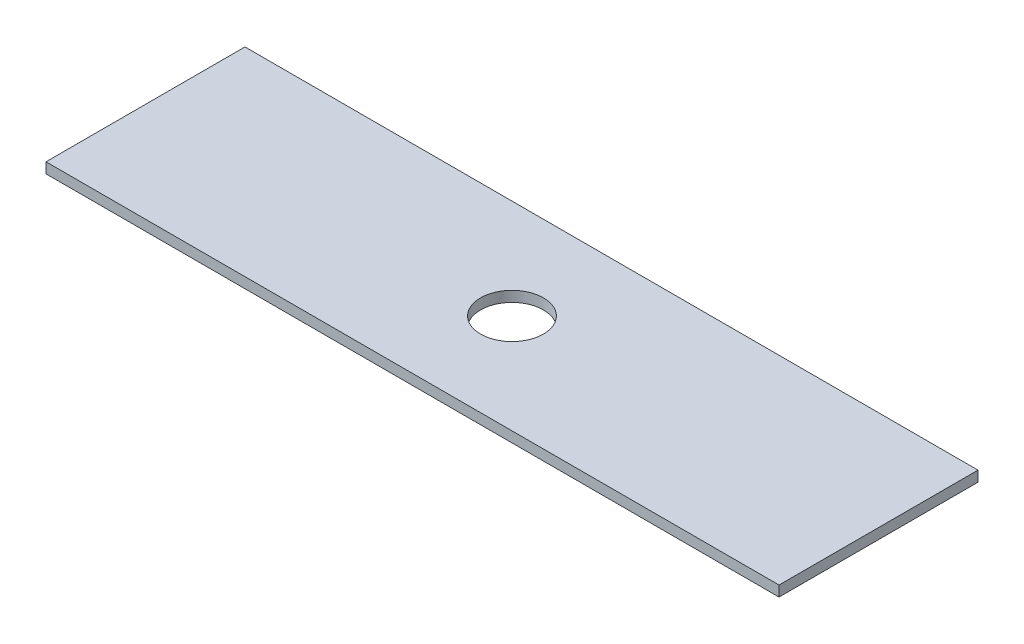
SolidWorks part; units mm, degrees
ref_plane "Alzado" through (0, 0, 0) normal (0, 0, 1) x (1, 0, 0)
ref_plane "Planta" through (0, 0, 0) normal (0, 1, 0) x (1, 0, 0)
ref_plane "Vista lateral" through (0, 0, 0) normal (1, 0, 0) x (0, 0, -1)
sketch "Croquis1" plane through (0, 0, 0) normal (0, 1, 0) x (1, 0, 0)
  line L1 (-350, -95) -> (350, -95)
  line L2 (-350, -95) -> (-350, 95)
  line L3 (-350, 95) -> (350, 95)
  line L4 (350, -95) -> (350, 95)
  line L5 (-350, -95) -> (350, 95) construction
  line L6 (-350, 95) -> (350, -95) construction
  point P0 (0, 0)
  dimension "D1" = 700
  dimension "D2" = 190
extrude "Saliente-Extruir1" add sketch "Croquis1" along normal blind 10
sketch "Croquis2" plane through (0, 10, 0) normal (0, 1, 0) x (1, 0, 0)
  line L0 (350, 95) -> (-350, 95) construction
  line L1 (350, -95) -> (350, 95) construction
  line L2 (-350, -95) -> (350, -95) construction
  circle A0 centre (0, 0) radius 30
  point P3 (0, 95)
  dimension "D1" = 95
  dimension "D3" = 95
  dimension "D2" = 350
extrude "Cortar-Extruir1" cut sketch "Croquis2" against normal up to surface (10 mm away) up to face at (0, 0, 0)
